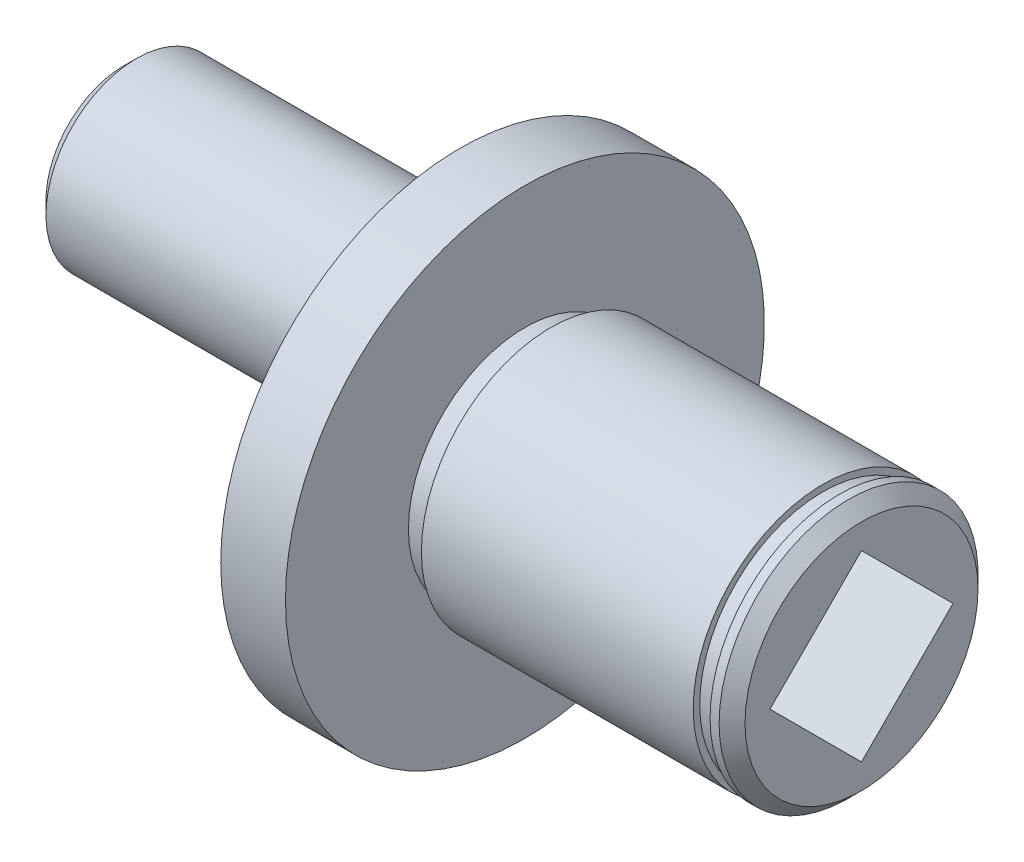
SolidWorks part; units mm, degrees
ref_plane "face" through (0, 0, 0) normal (0, 0, 1) x (1, 0, 0)
ref_plane "dessus" through (0, 0, 0) normal (0, 1, 0) x (1, 0, 0)
ref_plane "droite" through (0, 0, 0) normal (1, 0, 0) x (0, 0, -1)
sketch "Esquisse1" plane through (0, 0, 0) normal (0, 0, 1) x (1, 0, 0)
  line L14 (0, 0) -> (0, 18.5)
  line L15 (0, 18.5) -> (5, 18.5)
  line L16 (5, 18.5) -> (5, 9)
  line L17 (5, 9) -> (7, 9)
  line L18 (7, 9) -> (7, 10)
  line L19 (7, 10) -> (28, 10)
  line L20 (30, 10) -> (31, 9)
  line L21 (31, 9) -> (31, 0)
  line L22 (0, 0) -> (43.0051, 0) construction
  line L23 (0, 0) -> (31, 0)
  line L24 (29.3, 10) -> (29.3, 9.5)
  line L25 (29.3, 9.5) -> (28, 9.5)
  line L26 (28, 9.5) -> (28, 10)
  line L27 (29.3, 10) -> (30, 10)
  dimension "D1" = 5
  dimension "D2" = 18.5
  dimension "D3" = 10
  dimension "D4" = 9
  dimension "D5" = 1
  dimension "D6" = 9.5
  dimension "D7" = 9
  dimension "D8" = 10
  dimension "D9" = 2
  dimension "D10" = 1.3
  dimension "D11" = 31
  dimension "D12" = 0.7
  dimension "D13" = 1.7
revolve "Base-Révolution" add sketch "Esquisse1" angle 360 about L22
sketch "Esquisse2" plane through (0, 0, 0) normal (0, 0, 1) x (1, 0, 0)
  line L0 (0, 5) -> (-26, 5) construction
  line L1 (-26, 5) -> (-26, 11)
  line L2 (-26, 11) -> (-25, 12)
  line L3 (-25, 12) -> (-2, 12)
  line L5 (-2, 12) -> (-2, 11)
  line L6 (-2, 11) -> (0, 11)
  line L7 (0, 11) -> (0, 5)
  line L8 (0, 5) -> (-26, 5)
  dimension "D1" = 5
  dimension "D2" = 6
  dimension "D3" = 1
  dimension "D4" = 1
  dimension "D5" = 23
  dimension "D6" = 26
  dimension "D7" = 1
  dimension "D8" = 2
revolve "Boss.-Révol.1" add sketch "Esquisse2" angle 360 about L0
hole_wizard "Perçage5" positions "Esquisse15" profile "Esquisse14" legacy
sketch "Esquisse15" plane through (31, 0, 0) normal (1, 0, 0) x (0, 0, -1)
  point P0 (0, 0)
sketch "Esquisse14" plane through (31, 0, 0) normal (0, 1, 0) x (0, 0, -1)
  line L0 (0, 0) -> (0, 20.0043)
  line L1 (0, 20.0043) -> (5, 17)
  line L2 (5, 17) -> (5, 0)
  line L4 (5, 0) -> (0, 0)
  line L6 (0, 20.0043) -> (-5, 17) construction
  line L7 (0, -4.2442) -> (0, 117.3081) construction
  dimension "Diamètre" = 10
  dimension "Profondeur" = 17
  dimension "Angle" = 118
sketch "Esquisse5" plane through (31, 0.9187, 3.1954) normal (1, 0, 0) x (0, 0, -1)
  line L0 (-3.8757, -0.9187) -> (3.1954, 6.1524)
  line L1 (-3.8757, -0.9187) -> (3.1954, -7.9897)
  line L2 (3.1954, 6.1524) -> (10.2664, -0.9187)
  line L3 (3.1954, -7.9897) -> (10.2664, -0.9187)
  dimension "D3" = 7.0711
  dimension "D1" = 10
  dimension "D2" = 10
extrude "Enlèv. mat.-Extru.1" cut sketch "Esquisse5" against normal blind 12
